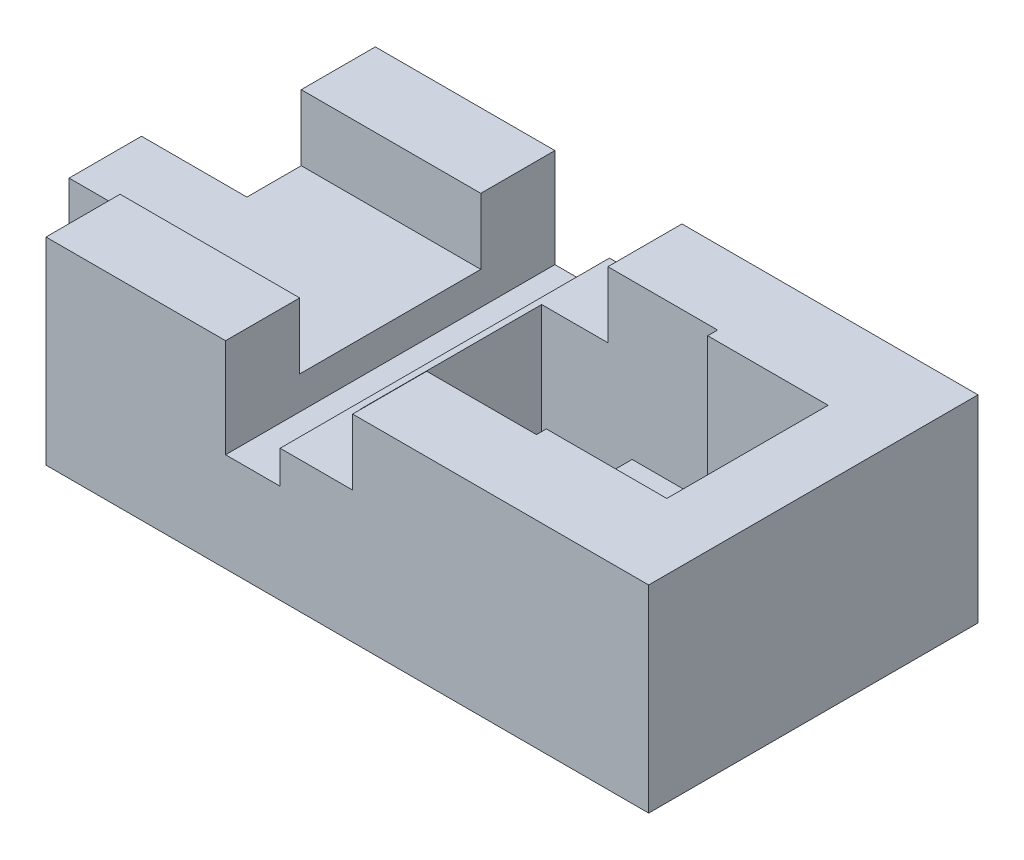
SolidWorks part; units mm, degrees
ref_plane "Front Plane" through (0, 0, 0) normal (0, 0, 1) x (1, 0, 0)
ref_plane "Top Plane" through (0, 0, 0) normal (0, 1, 0) x (1, 0, 0)
ref_plane "Right Plane" through (0, 0, 0) normal (1, 0, 0) x (0, 0, -1)
sketch "Sketch1" plane through (0, 0, 0) normal (0, 1, 0) x (1, 0, 0)
  line L1 (-9.75, -5) -> (9.75, -5)
  line L2 (-9.75, -5) -> (-9.75, 5)
  line L3 (-9.75, 5) -> (9.75, 5)
  line L4 (9.75, -5) -> (9.75, 5)
  line L5 (-9.75, -5) -> (9.75, 5) construction
  line L6 (-9.75, 5) -> (9.75, -5) construction
  point P0 (0, 0)
  dimension "D1" = 19.5
  dimension "D2" = 10
extrude "Boss-Extrude1" add sketch "Sketch1" along normal blind 4
sketch "Sketch2" plane through (0, 4, 0) normal (0, 1, 0) x (1, 0, 0)
  line L0 (9.75, -5) -> (9.75, 5) construction
  line L1 (9.75, 2.75) -> (0.75, 2.75)
  line L2 (9.75, 2.75) -> (9.75, -2.75)
  line L3 (9.75, -2.75) -> (0.75, -2.75)
  line L4 (0.75, 2.75) -> (0.75, -2.75)
  line L5 (-9.75, 5) -> (-9.75, -5) construction
  point P8 (-9.75, 0)
  point P9 (0.75, 0)
  dimension "D1" = 5.5
  dimension "D2" = 9
extrude "Cut-Extrude1" cut sketch "Sketch2" against normal blind 2.7
sketch "Sketch3" plane through (0, 4, 0) normal (0, 1, 0) x (1, 0, 0)
  line L0 (-6.55, 1.1) -> (-6.55, -1.1) construction
  line L1 (-9.75, 5) -> (-6.55, 5)
  line L2 (-9.75, 5) -> (-9.75, 1.1)
  line L3 (-9.75, 1.1) -> (-6.55, 1.1)
  line L4 (-6.55, 5) -> (-6.55, 1.1)
  line L5 (-9.75, -5) -> (-6.55, -5)
  line L6 (-9.75, -5) -> (-9.75, -1.1)
  line L7 (-9.75, -1.1) -> (-6.55, -1.1)
  line L8 (-6.55, -5) -> (-6.55, -1.1)
  line L9 (9.75, -2.75) -> (9.75, 2.75) construction
  line L10 (0.75, 2.75) -> (0.75, -2.75) construction
  point P12 (9.75, 0)
  point P13 (-6.55, 0)
  dimension "D1" = 2.2
  dimension "D2" = 7.3
extrude "Cut-Extrude2" cut sketch "Sketch3" against normal through all
sketch "Sketch4" plane through (0, 1.3, 0) normal (0, 1, 0) x (1, 0, 0)
  line L0 (0.75, -2.75) -> (9.75, -2.75) construction
  line L1 (0.75, 2.75) -> (2.4979, 2.75)
  line L2 (0.75, 2.75) -> (0.75, -2.75)
  line L3 (0.75, -2.75) -> (2.4979, -2.75)
  line L4 (2.4979, 2.75) -> (2.4979, -2.75)
extrude "Cut-Extrude3" cut sketch "Sketch4" against normal through all
chamfer "Chamfer2" distance 1 angle 45 1 edges at (2.4979, 1.3, 0)
sketch "Sketch5" plane through (9.75, 0, 0) normal (1, 0, 0) x (0, 0, -1)
  line L1 (5, 0) -> (-5, 0)
  line L2 (5, 0) -> (5, 4)
  line L3 (5, 4) -> (-5, 4)
  line L4 (-5, 0) -> (-5, 4)
extrude "Boss-Extrude2" add sketch "Sketch5" along normal blind 2
sketch "Sketch6" plane through (0, 1.3, 0) normal (0, 1, 0) x (1, 0, 0)
  line L0 (3.4979, -2.75) -> (9.75, -2.75) construction
  line L1 (9.75, 2.75) -> (8.0029, 2.75)
  line L2 (9.75, 2.75) -> (9.75, -2.75)
  line L3 (9.75, -2.75) -> (8.0029, -2.75)
  line L4 (8.0029, 2.75) -> (8.0029, -2.75)
extrude "Boss-Extrude3" add sketch "Sketch6" along normal blind 1.5
sketch "Sketch7" plane through (0, 4, 0) normal (0, 1, 0) x (1, 0, 0)
  line L0 (2.7607, 2.75) -> (2.7607, 5)
  line L1 (9.75, 2.75) -> (0.75, 2.75) construction
  line L2 (11.75, 5) -> (-6.55, 5) construction
  line L3 (2.7607, 5) -> (11.75, 5)
  line L4 (11.75, 5) -> (11.75, -5)
  line L5 (11.75, -5) -> (2.7607, -5)
  line L6 (-6.55, -5) -> (11.75, -5) construction
  line L7 (2.7607, -5) -> (2.7607, -2.75)
  line L8 (0.75, -2.75) -> (9.75, -2.75) construction
  line L9 (2.7607, -2.75) -> (9.75, -2.75)
  line L10 (9.75, -2.75) -> (9.75, 2.75)
  line L11 (9.75, 2.75) -> (2.7607, 2.75)
extrude "Boss-Extrude4" add sketch "Sketch7" along normal blind 2
sketch "Sketch9" plane through (0, 6, 0) normal (0, 1, 0) x (1, 0, 0)
  line L0 (9.75, 2.75) -> (9.75, 2.45)
  line L1 (9.75, 2.75) -> (9.75, -2.75) construction
  line L2 (9.75, 2.45) -> (6.0926, 2.45)
  line L3 (6.0926, 2.45) -> (6.0926, 2.75)
  line L4 (6.0926, 2.75) -> (9.75, 2.75)
  line L5 (9.75, -2.75) -> (6.0926, -2.75)
  line L6 (9.75, -2.75) -> (2.7607, -2.75) construction
  line L7 (6.0926, -2.75) -> (6.0926, -2.45)
  line L8 (6.0926, -2.45) -> (9.75, -2.45)
  line L9 (9.75, -2.45) -> (9.75, -2.75)
  dimension "D1" = 0.3
extrude "Boss-Extrude5" add sketch "Sketch9" against normal through all
sketch "Sketch10" plane through (0, 4, 0) normal (0, 1, 0) x (1, 0, 0)
  line L0 (2.7607, 2.75) -> (0.75, 2.75) construction
  line L1 (-6.55, 5) -> (-0.735, 5)
  line L2 (-6.55, 5) -> (-6.55, 2.75)
  line L3 (-6.55, 2.75) -> (-0.735, 2.75)
  line L4 (-0.735, 5) -> (-0.735, 2.75)
  line L5 (-6.55, -5) -> (-1.0976, -5)
  line L6 (-6.55, -5) -> (-6.55, -2.75)
  line L7 (-6.55, -2.75) -> (-1.0976, -2.75)
  line L8 (-1.0976, -5) -> (-1.0976, -2.75)
extrude "Boss-Extrude6" add sketch "Sketch10" along normal up to surface (2 mm away) up to face at (6.5344, 6, 0)
sketch "Sketch12" plane through (0, 4, 0) normal (0, 1, 0) x (1, 0, 0)
  line L0 (2.7607, 5) -> (-0.735, 5) construction
  line L1 (-1.0976, -5) -> (0.5589, -5)
  line L2 (-1.0976, -5) -> (-1.0976, 5)
  line L3 (-1.0976, 5) -> (0.5589, 5)
  line L4 (0.5589, -5) -> (0.5589, 5)
extrude "Cut-Extrude4" cut sketch "Sketch12" against normal blind 1 and the other way blind 3.8
